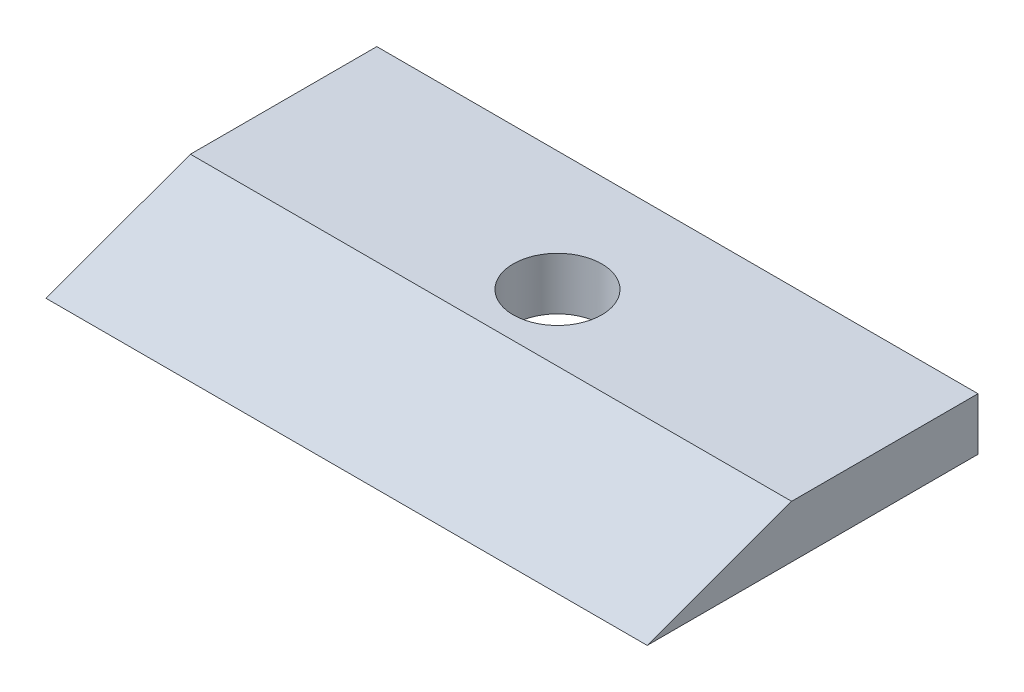
SolidWorks part; units mm, degrees
material "Oak"
ref_plane "Front Plane" through (0, 0, 0) normal (0, 0, 1) x (1, 0, 0)
ref_plane "Top Plane" through (0, 0, 0) normal (0, 1, 0) x (1, 0, 0)
ref_plane "Right Plane" through (0, 0, 0) normal (1, 0, 0) x (0, 0, -1)
sketch "Sketch1" plane through (0, 0, 0) normal (1, 0, 0) x (0, 0, -1)
  line L0 (0, 0) -> (8.7302, 3.18)
  line L1 (8.7302, 3.18) -> (20, 3.18)
  line L2 (20, 3.18) -> (20, 0.005)
  line L3 (20, 0.005) -> (0, 0)
  dimension "D1" = 3.175
  dimension "D2" = 20
  dimension "D3" = 3.18
  dimension "D4" = 20
extrude "Boss-Extrude1" add sketch "Sketch1" along normal blind 36.35
sketch "Sketch2" plane through (0, 3.18, 0) normal (0, 1, 0) x (1, 0, 0)
  line L0 (0, 20) -> (0, 8.7302) construction
  line L1 (36.35, 20) -> (0, 20) construction
  circle A0 centre (18.175, 12.75) radius 2.675
  dimension "D3" = 5.35
  dimension "D1" = 18.175
  dimension "D2" = 7.25
extrude "Cut-Extrude1" cut sketch "Sketch2" against normal blind 15
